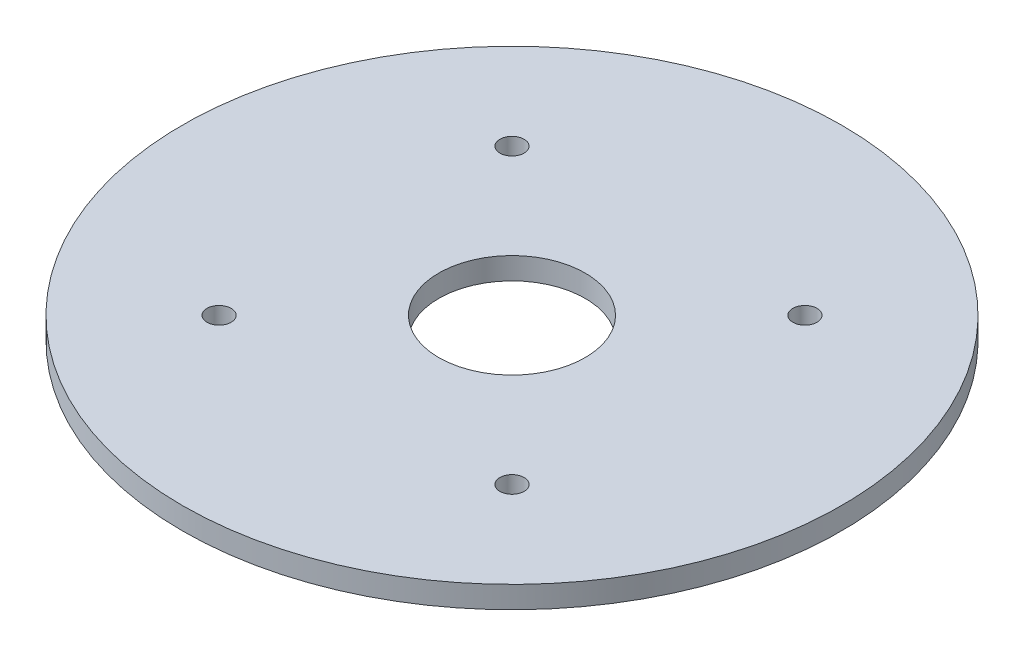
SolidWorks part; units mm, degrees
ref_plane "Front Plane" through (0, 0, 0) normal (0, 0, 1) x (1, 0, 0)
ref_plane "Top Plane" through (0, 0, 0) normal (0, 1, 0) x (1, 0, 0)
ref_plane "Right Plane" through (0, 0, 0) normal (1, 0, 0) x (0, 0, -1)
sketch "Sketch1" plane through (0, 0, 0) normal (0, 1, 0) x (1, 0, 0)
  circle A0 centre (0, 0) radius 45
  circle A1 centre (0, 0) radius 10
  dimension "D1" = 90
  dimension "D2" = 20
extrude "Boss-Extrude1" add sketch "Sketch1" along normal mid plane 3
sketch "Sketch2" plane through (0, 1.5, 0) normal (0, 1, 0) x (1, 0, 0)
  line L1 (20, 20) -> (-20, 20) construction
  line L2 (20, 20) -> (20, -20) construction
  line L3 (20, -20) -> (-20, -20) construction
  line L4 (-20, 20) -> (-20, -20) construction
  line L5 (20, 20) -> (-20, -20) construction
  line L6 (20, -20) -> (-20, 20) construction
  circle A0 centre (-20, -20) radius 1.65
  circle A1 centre (-20, 20) radius 1.65
  circle A2 centre (20, 20) radius 1.65
  circle A3 centre (20, -20) radius 1.65
  point P0 (0, 0)
  dimension "D3" = 3.3
  dimension "D1" = 40
  dimension "D2" = 40
extrude "Cut-Extrude1" cut sketch "Sketch2" against normal blind 10
